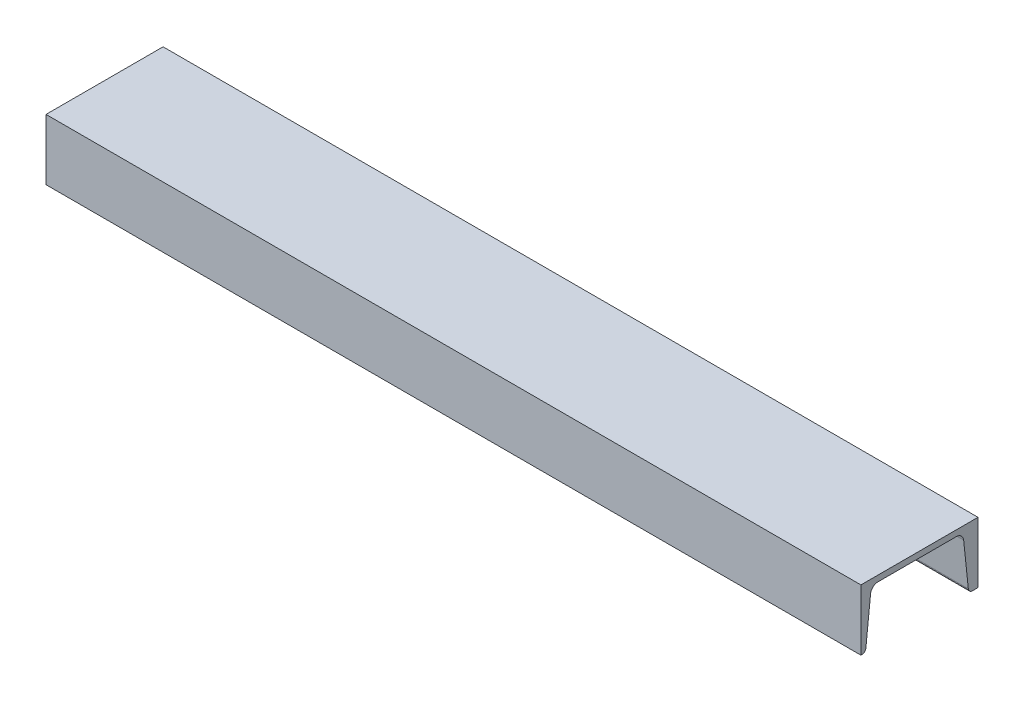
SolidWorks part; units mm, degrees
ref_plane "Front Plane" through (0, 0, 0) normal (0, 0, 1) x (1, 0, 0)
ref_plane "Top Plane" through (0, 0, 0) normal (0, 1, 0) x (1, 0, 0)
ref_plane "Right Plane" through (0, 0, 0) normal (1, 0, 0) x (0, 0, -1)
sketch "Sketch1" plane through (0, 0, 0) normal (0, 0, 1) x (1, 0, 0)
  line L0 (0, 0) -> (-870, 0)
  dimension "D1" = 870
other "C channel 120 X 12(1)"
ref_plane "Plane1" through (0, 0, 0) normal (-1, 0, 0) x (0, -1, 0)
sketch "Sketch12" plane through (0, 0, 0) normal (-1, 0, 0) x (0, -1, 0)
  line L0 (65, 125) -> (0, 125)
  line L1 (65, 0) -> (0, 0)
  line L2 (0, 125) -> (0, 0)
  line L6 (65, 125) -> (65, 124.1647)
  line L7 (65, 0) -> (65, 5.8453)
  line L12 (6.3, 106.74) -> (6.3, 23.27)
  line L17 (13.4638, 114.6962) -> (60.9704, 119.6893)
  line L18 (13.4638, 15.3138) -> (60.9704, 10.3207)
  arc A0 (60.9704, 119.6893) -> (65, 124.1647) centre (60.5, 124.1647) ccw
  arc A1 (60.9704, 10.3207) -> (65, 5.8453) centre (60.5, 5.8453) cw
  arc A9 (6.3, 23.27) -> (13.4638, 15.3138) centre (14.3, 23.27) ccw
  arc A10 (6.3, 106.74) -> (13.4638, 114.6962) centre (14.3, 106.74) cw
  point P8 (0, 62.5)
  point P9 (6.3, 65.005)
  point P10 (32.5, 125)
  point P11 (32.5, 0)
  point P12 (65, 9.8971)
  point P13 (65, 120.1129)
  point P14 (0, 0)
  dimension "D4" = 4.5
  dimension "RI" = 8
  dimension "D2" = 6
  dimension "D3" = 18.26
  dimension "Depth" = 125
  dimension "BF" = 65
  dimension "TW" = 6.3
  dimension "d1" = 83.47
